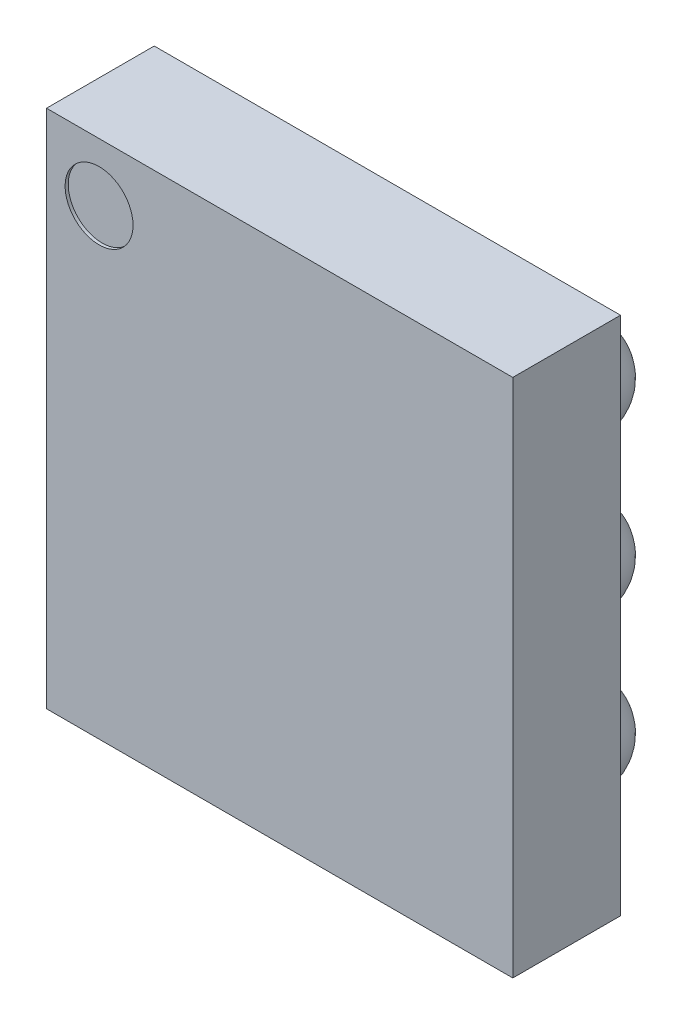
SolidWorks part; units mm, degrees
ref_plane "Front Plane" through (0, 0, 0) normal (0, 0, 1) x (1, 0, 0)
ref_plane "Top Plane" through (0, 0, 0) normal (0, 1, 0) x (1, 0, 0)
ref_plane "Right Plane" through (0, 0, 0) normal (1, 0, 0) x (0, 0, -1)
sketch "Sketch1" plane through (0, 0, 0) normal (0, 0, 1) x (1, 0, 0)
  line L1 (-0.7575, -0.845) -> (0.7575, -0.845)
  line L2 (-0.7575, -0.845) -> (-0.7575, 0.845)
  line L3 (-0.7575, 0.845) -> (0.7575, 0.845)
  line L4 (0.7575, -0.845) -> (0.7575, 0.845)
  line L5 (-0.7575, -0.845) -> (0.7575, 0.845) construction
  line L6 (-0.7575, 0.845) -> (0.7575, -0.845) construction
  point P0 (0, 0)
  dimension "D1" = 1.515
  dimension "D2" = 1.69
extrude "Boss-Extrude1" add sketch "Sketch1" along normal blind 0.35 from offset 0.24 contours L3 L4 L1 L2
sketch "Sketch2" plane through (0, 0, 0.59) normal (0, 0, 1) x (1, 0, 0)
  circle A0 centre (-0.5867, 0.656) radius 0.1103
  point P2 (-0.5867, 0.656)
extrude "Cut-Extrude1" cut sketch "Sketch2" against normal blind 0.01
ref_plane "Plane1" through (0.5, 0, 0) normal (1, 0, 0) x (0, 0, -1)
sketch "Sketch3" plane through (0.5, 0, 0) normal (1, 0, 0) x (0, 0, -1)
  line L0 (-0.24, 0.5) -> (-0.24, 0.3614)
  line L1 (-0.24, -0.845) -> (-0.24, 0.845) construction
  line L2 (-0.24, 0.5) -> (0, 0.5)
  line L3 (0, 0.5) -> (0, 0.3644) construction
  arc A0 (0, 0.5) -> (-0.24, 0.3614) centre (-0.16, 0.5) cw
  point P6 (-0.24, 0.344)
  dimension "D2" = 0.16
  dimension "D1" = 0.24
  dimension "D3" = 0.5
revolve "Revolve1" add sketch "Sketch3" angle 360 about L2
pattern_linear "LPattern1" count 3 spacing 0.5 along (-1, 0, 0) count 3 spacing 0.5 along (0, -1, 0) of "Revolve1"
